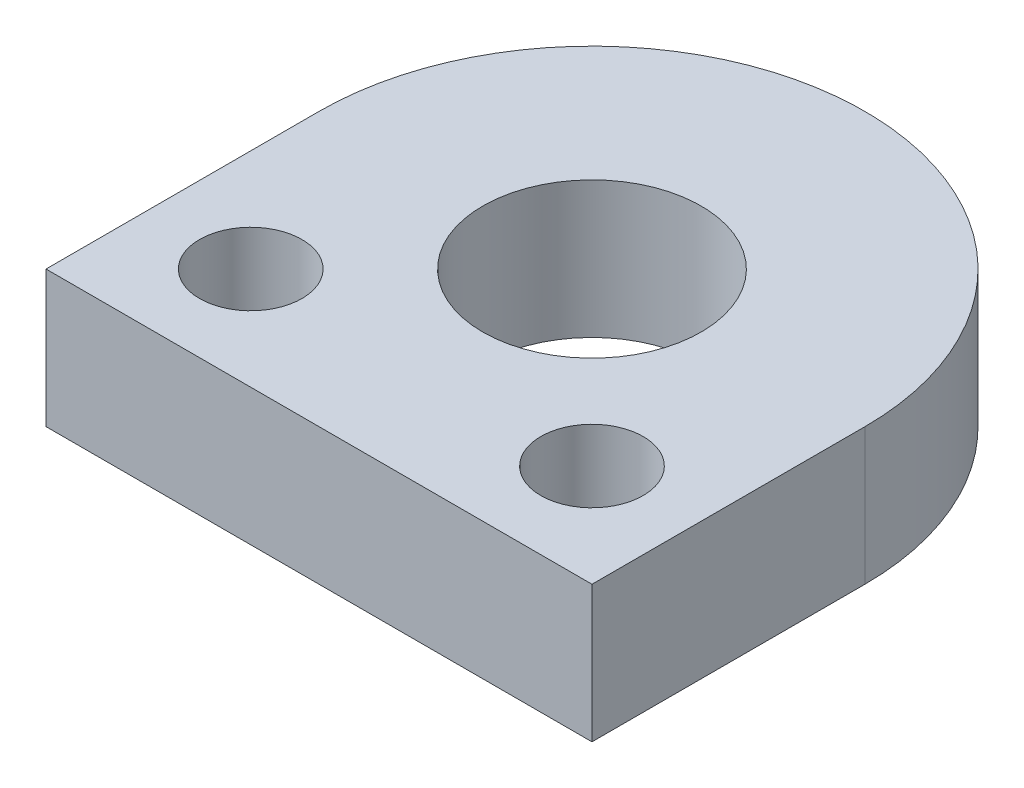
SolidWorks part; units mm, degrees
ref_plane "Front Plane" through (0, 0, 0) normal (0, 0, 1) x (1, 0, 0)
ref_plane "Top Plane" through (0, 0, 0) normal (0, 1, 0) x (1, 0, 0)
ref_plane "Right Plane" through (0, 0, 0) normal (1, 0, 0) x (0, 0, -1)
sketch "Sketch1" plane through (0, 0, 0) normal (0, 1, 0) x (1, 0, 0)
  line L1 (0, 0) -> (80, 0)
  line L2 (0, 0) -> (0, 40)
  line L3 (0, 40) -> (80, 40)
  line L4 (80, 0) -> (80, 40)
  circle A0 centre (40, 40) radius 40
  dimension "D1" = 80
  dimension "D2" = 40
extrude "Extrude1" add sketch "Sketch1" along normal blind 20
sketch "Sketch3" plane through (0, 20, 0) normal (0, 1, 0) x (1, 0, 0)
  circle A0 centre (40, 40) radius 16
  arc A1 (80, 40) -> (0, 40) centre (40, 40) ccw construction
  dimension "D1" = 32
extrude "Cut-Extrude1" cut sketch "Sketch3" against normal through all
sketch "Sketch7" plane through (0, 20, 0) normal (0, 1, 0) x (1, 0, 0)
  line L1 (40, 0) -> (40, 90) construction
  line L3 (0, 0) -> (80, 0) construction
  circle A0 centre (15, 15) radius 7.5
  dimension "D1" = 15
  dimension "D3" = 15
  dimension "D4" = 15
extrude "Cut-Extrude2" cut sketch "Sketch7" against normal through all
ref_point "Point1"
ref_plane "Plane1" through (40, 0, 0) normal (1, 0, 0) x (0, 0, -1)
mirror "Mirror1" about plane through (40, 0, 0) normal (1, 0, 0) of "Cut-Extrude2"
equation "\"D2@Sketch1\"=\"D1@Sketch1\" * 0.5"
equation "\"D1@Sketch3\"=\"D2@Sketch1\" * 0.8"
equation "\"D4@Sketch7\" = \"D3@Sketch7\""
